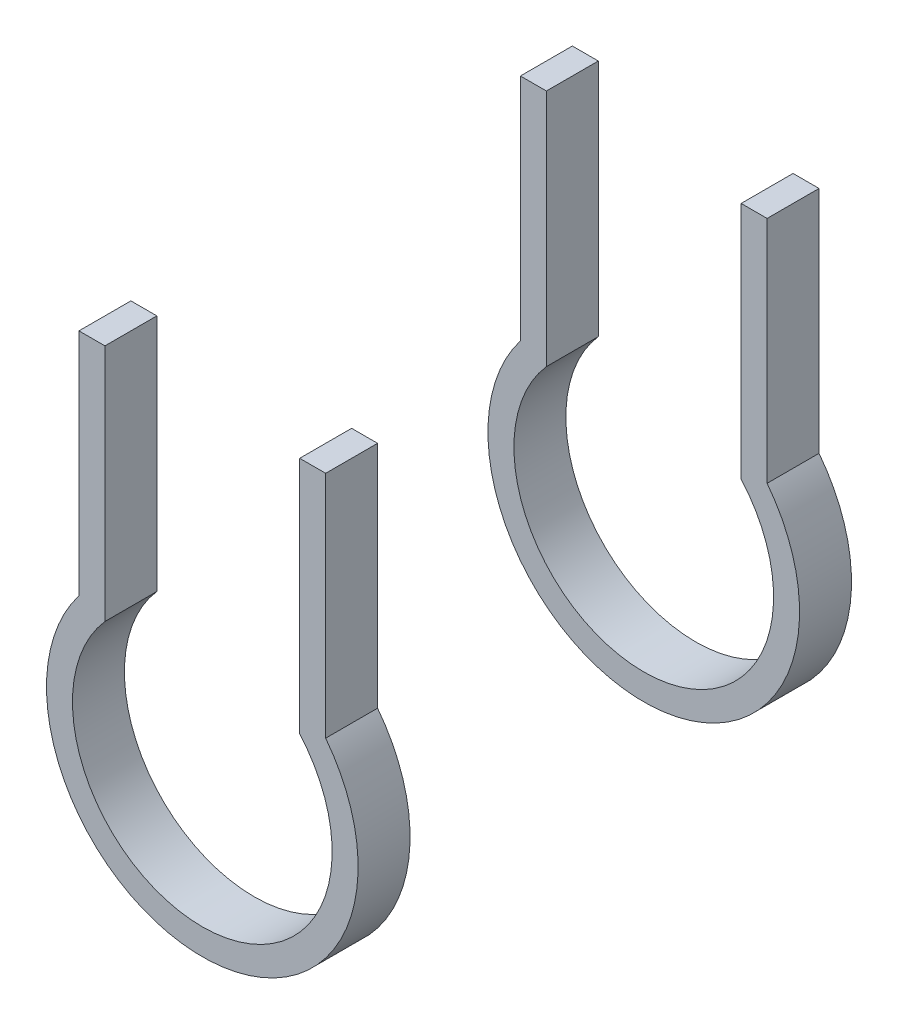
SolidWorks part; units mm, degrees
ref_plane "前视" through (0, 0, 0) normal (0, 0, 1) x (1, 0, 0)
ref_plane "上视" through (0, 0, 0) normal (0, 1, 0) x (1, 0, 0)
ref_plane "右视" through (0, 0, 0) normal (1, 0, 0) x (0, 0, -1)
sketch "草图1" plane through (0, 0, 0) normal (0, 0, 1) x (1, 0, 0)
  line L0 (0, 50) -> (0, -33.8705) construction
  line L1 (-19, 50) -> (-19, 14.6629)
  line L2 (19, 50) -> (19, 14.6629)
  line L3 (-15, 50) -> (-15, 13.2288)
  line L4 (-19, 50) -> (-19, -33.8705) construction
  line L5 (19, 50) -> (19, -33.8705) construction
  line L6 (15, 50) -> (15, 13.2288)
  line L7 (-19, 50) -> (-15, 50)
  line L8 (15, 50) -> (19, 50)
  arc A0 (-19, 14.6629) -> (19, 14.6629) centre (0, 0) ccw
  arc A1 (-15, 13.2288) -> (15, 13.2288) centre (0, 0) ccw
  dimension "D1" = 48
  dimension "D5" = 50
  dimension "D2" = 19
  dimension "D3" = 19
  dimension "D4" = 4
extrude "凸台-拉伸1" add sketch "草图1" along normal blind 76
ref_plane "基准面2" through (0, 0, 38) normal (0, 0, 1) x (1, 0, 0)
sketch "草图3" plane through (0, 0, 38) normal (0, 0, 1) x (1, 0, 0)
  line L0 (25.7419, -74.843) -> (-36.6578, -74.843)
  line L1 (-36.6578, 55.157) -> (25.7419, 55.157)
  line L2 (-36.6578, 55.157) -> (-36.6578, -74.843)
  line L4 (25.7419, 55.157) -> (25.7419, -74.843)
  dimension "D1" = 130
extrude "切除-拉伸2" cut sketch "草图3" against normal blind 30 and the other way blind 30
sketch "草图4" plane through (0, 0, 38) normal (0, 0, 1) x (1, 0, 0)
  line L0 (-22.383, 13.2288) -> (22.383, 13.2288)
  arc A0 (-22.383, 13.2288) -> (22.383, 13.2288) centre (0, 0) ccw
  dimension "D1" = 26
